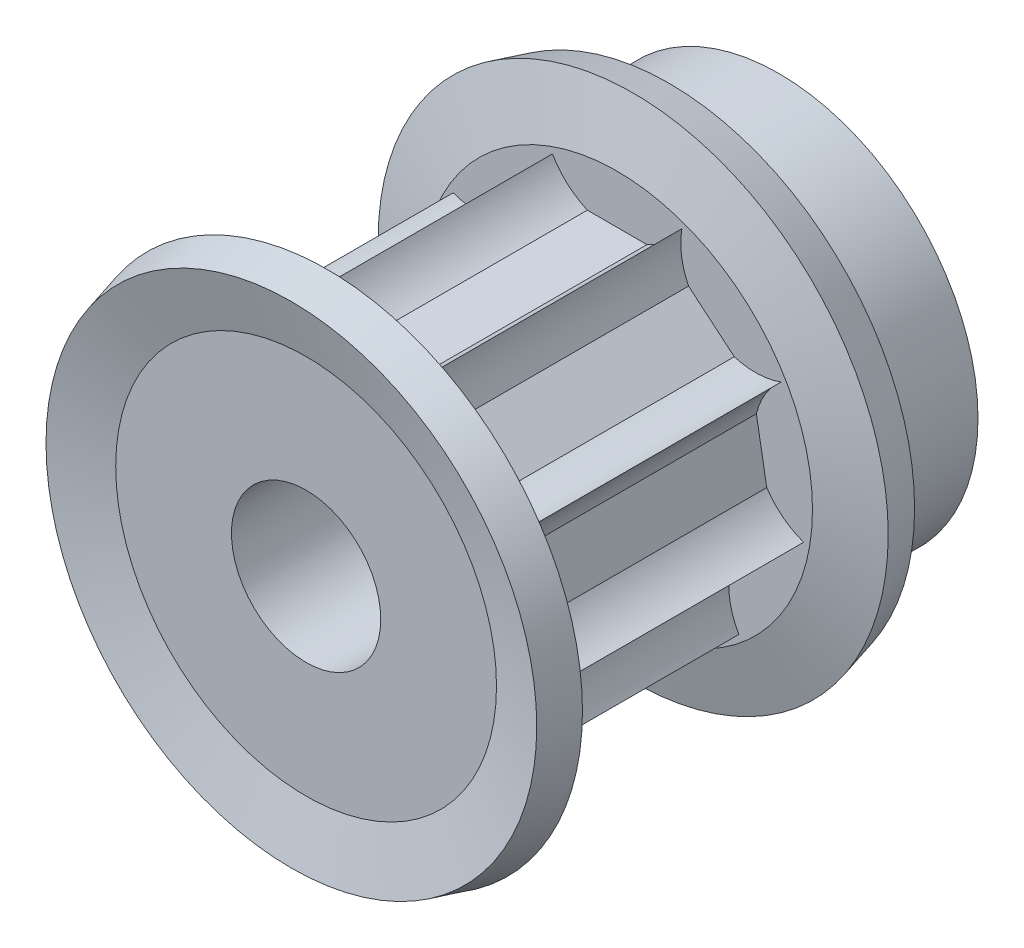
SolidWorks part; units mm, degrees
ref_plane "Front Plane" through (0, 0, 0) normal (0, 0, 1) x (1, 0, 0)
ref_plane "Top Plane" through (0, 0, 0) normal (0, 1, 0) x (1, 0, 0)
ref_plane "Right Plane" through (0, 0, 0) normal (1, 0, 0) x (0, 0, -1)
ref_axis "Axis1" through (0, 0, 55) along (0, 0, -1)
sketch "Sketch1" plane through (0, 0, 0) normal (1, 0, 0) x (0, 0, -1)
  line L0 (0, 3) -> (0, 10)
  line L1 (0, 10) -> (14, 10)
  line L2 (14, 10) -> (14, 8)
  line L3 (14, 8) -> (19, 8)
  line L4 (19, 8) -> (19, 3)
  line L5 (19, 3) -> (0, 3)
  line L6 (-55, 0) -> (55, 0) construction
  dimension "D1" = 10
  dimension "D2" = 14
  dimension "D3" = 5
  dimension "D4" = 3
  dimension "D5" = 5
revolve "Revolve1" add sketch "Sketch1" angle 360 about axis through (0, 0, 55) along (0, 0, -1)
sketch "Sketch2" plane through (0, 0, 0) normal (0, 0, 1) x (1, 0, 0)
  line L0 (3.6743, 8.6421) -> (3.75, 8.6421)
  line L1 (-3.75, 8.6421) -> (-3.6743, 8.6421)
  line L2 (-3.75, 8.6421) -> (-3.75, 10.6421)
  line L3 (-3.75, 10.6421) -> (3.75, 10.6421)
  line L4 (3.75, 8.6421) -> (3.75, 10.6421)
  line L5 (1.199, 5.892) -> (-1.199, 5.892)
  arc A0 (-2.9394, 8.0421) -> (-1.199, 5.892) centre (0, 8.642) ccw
  arc A1 (2.9394, 8.0421) -> (3.6743, 8.6421) centre (3.6743, 7.8921) cw
  arc A2 (-2.9394, 8.0421) -> (-3.6743, 8.6421) centre (-3.6743, 7.8921) ccw
  arc A3 (1.199, 5.892) -> (2.9394, 8.0421) centre (0, 8.642) ccw
  point P12 (3, 8.6421)
  point P19 (-3, 8.6421)
  dimension "D1" = 3
  dimension "D4" = 0.75
  dimension "D5" = 0.75
  dimension "D2" = 7.5
  dimension "D3" = 2
  dimension "D6" = 2.75
extrude "Cut-Extrude1" cut sketch "Sketch2" against normal up to surface (14 mm away) up to face at (10, 0, -14)
pattern_circular "CirPattern17" count 9 over 360 about axis through (0, 0, 0) along (0, 0, 1) of "Cut-Extrude1"
sketch "Sketch3" plane through (0, 0, 0) normal (1, 0, 0) x (0, 0, -1)
  line L0 (1.5, 7.8486) -> (0.0511, 7.4604) construction
  line L1 (0, 3.8037) -> (1.5, 3.8037)
  line L2 (0, 3.8037) -> (0, 7.8486)
  line L3 (0, 7.8486) -> (1.5, 7.8486) construction
  line L4 (1.5, 3.8037) -> (1.5, 7.8486)
  line L5 (1.5, 7.8486) -> (0.8569, 10.2486)
  line L6 (0.0511, 7.4604) -> (-0.592, 9.8604)
  line L7 (0.8569, 10.2486) -> (-0.592, 9.8604)
  line L9 (0, 7.1486) -> (14, 7.1486) construction
  line L10 (7, 12.132) -> (7, -8.9897) construction
  line L11 (14, 7.8486) -> (12.5, 7.8486) construction
  line L12 (12.5, 7.8486) -> (13.9489, 7.4604) construction
  line L13 (13.1431, 10.2486) -> (14.592, 9.8604)
  line L14 (13.9489, 7.4604) -> (14.592, 9.8604)
  line L15 (12.5, 7.8486) -> (13.1431, 10.2486)
  line L16 (12.5, 3.8037) -> (12.5, 7.8486)
  line L17 (14, 3.8037) -> (14, 7.8486)
  line L18 (14, 3.8037) -> (12.5, 3.8037)
  dimension "D1" = 1.5
  dimension "D3" = 1.5
  dimension "D4" = 2.4
  dimension "D5" = 165
  dimension "D6" = 0.7
revolve "Revolve2" add sketch "Sketch3" angle 360 about axis through (0, 0, 55) along (0, 0, -1)
sketch "Sketch6" plane through (0, 0, 0) normal (0, 1, 0) x (1, 0, 0)
  line L0 (0, -55) -> (0, 55) construction
  circle A0 centre (0, 16.7598) radius 1.5
  dimension "D1" = 3
extrude "Cut-Extrude2" cut sketch "Sketch6" against normal blind 10 contours A0
ref_plane "Plane1" through (0, 0, -7) normal (0, 0, 1) x (1, 0, 0)
sketch "Sketch7" plane through (0, 0, -7) normal (0, 0, 1) x (1, 0, 0)
  circle A0 centre (0, 0) radius 9
  dimension "D1" = 18
